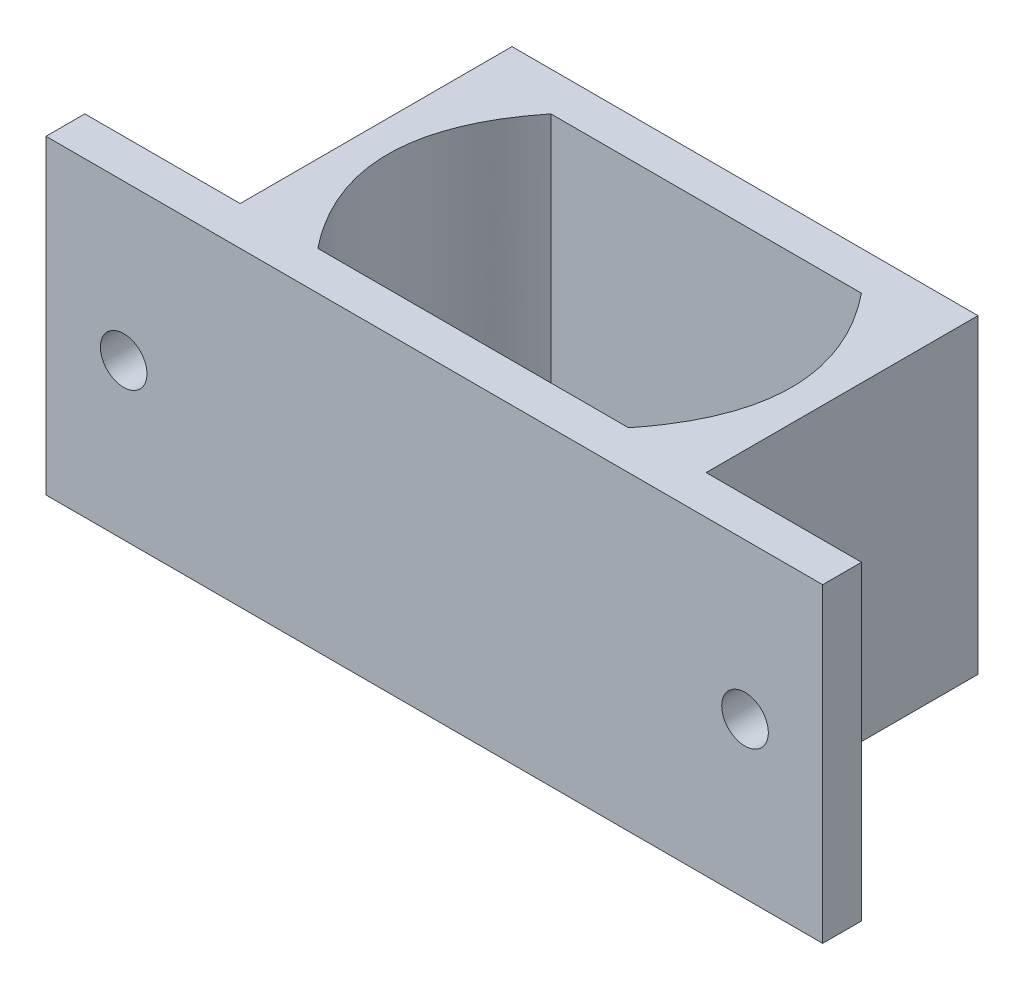
SolidWorks part; units mm, degrees
ref_plane "Front Plane" through (0, 0, 0) normal (0, 0, 1) x (1, 0, 0)
ref_plane "Top Plane" through (0, 0, 0) normal (0, 1, 0) x (1, 0, 0)
ref_plane "Right Plane" through (0, 0, 0) normal (1, 0, 0) x (0, 0, -1)
sketch "Sketch1" plane through (0, 0, 0) normal (0, 1, 0) x (1, 0, 0)
  line L5 (-8.13, 7.5) -> (11.87, 7.5)
  line L8 (-8.13, 7.5) -> (-8.13, -7.5)
  line L9 (11.87, 7.5) -> (11.87, -7.5)
  line L10 (-8.13, 0) -> (-11.13, 0)
  line L11 (11.87, 0) -> (14.87, 0)
  line L12 (-8.13, -7.5) -> (11.87, -7.5)
  line L13 (-8.13, 7.5) -> (-13.13, 7.5)
  line L14 (-13.13, 7.5) -> (-13.13, 10)
  line L15 (11.87, -7.5) -> (16.87, -7.5)
  line L16 (16.87, -7.5) -> (16.87, -10)
  line L18 (-13.13, 10) -> (16.87, 10)
  line L19 (-13.13, 10) -> (-13.13, -10)
  line L20 (-13.13, -10) -> (16.87, -10)
  line L21 (16.87, 10) -> (16.87, -10)
  spline S0 degree 2 poles (-8.13, 7.5) (-14.13, 0) (-8.13, -7.5) knots 0 0 0 1 1 1
  spline S1 degree 2 poles (11.87, 7.5) (17.87, 0) (11.87, -7.5) knots 0 0 0 1 1 1
extrude "Boss-Extrude3" add sketch "Sketch1" along normal blind 20 contours S0 L13 L19 L20 L16 L15 L12 | L5 S1 L15 L21 L18 L14 L13
sketch "Sketch2" plane through (0, 20, 0) normal (0, 1, 0) x (1, 0, 0)
  line L0 (-13.13, -10) -> (-23.13, -10)
  line L1 (-23.13, -10) -> (-23.13, -7.5)
  line L2 (-23.13, -7.5) -> (-13.13, -7.5)
  line L3 (-13.13, 10) -> (-13.13, -10) construction
  line L4 (16.87, -10) -> (26.87, -10)
  line L5 (26.87, -10) -> (26.87, -7.5)
  line L6 (26.87, -7.5) -> (16.87, -7.5)
  line L8 (16.87, 10) -> (-13.13, 10)
  line L9 (-13.13, 10) -> (-13.13, -10)
  line L10 (-13.13, -10) -> (16.87, -10)
  line L11 (16.87, -10) -> (16.87, 10)
  line L12 (16.87, 10) -> (-13.13, 10)
  line L13 (-13.13, 10) -> (-13.13, -7.5)
  line L14 (-13.13, -10) -> (16.87, -10)
  line L15 (16.87, -10) -> (16.87, 10)
  line M9 (-13.13, 10) -> (-13.13, -10)
  line M11 (16.87, -10) -> (16.87, 10)
  dimension "D1" = 0
extrude "Boss-Extrude6" add sketch "Sketch2" against normal blind 20 contours L5 L6 L4 M11 | L2 L1 L0 M9
sketch "Sketch5" plane through (0, 0, 7.5) normal (0, 0, -1) x (-1, 0, 0)
  line L0 (23.13, 10) -> (18.13, 10)
  line L1 (23.13, 0) -> (23.13, 20) construction
  line L2 (-26.87, 10) -> (-21.87, 10)
  line L3 (-26.87, 0) -> (-26.87, 20) construction
  circle A0 centre (18.13, 10) radius 1.5
  circle A1 centre (-21.87, 10) radius 1.5
extrude "Cut-Extrude1" cut sketch "Sketch5" against normal blind 20
